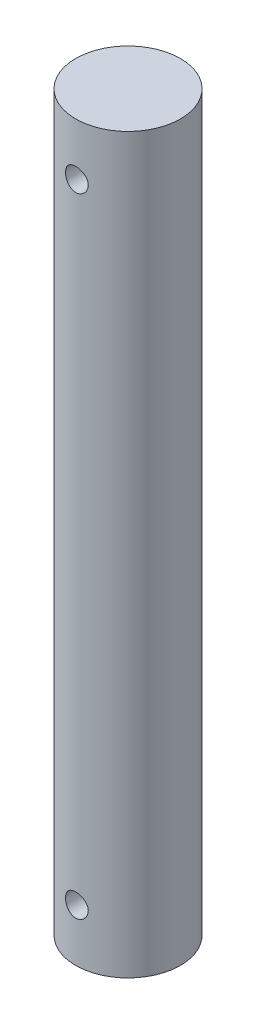
SolidWorks part; units mm, degrees
ref_plane "Front Plane" through (0, 0, 0) normal (0, 0, 1) x (1, 0, 0)
ref_plane "Top Plane" through (0, 0, 0) normal (0, 1, 0) x (1, 0, 0)
ref_plane "Right Plane" through (0, 0, 0) normal (1, 0, 0) x (0, 0, -1)
sketch "Sketch1" plane through (0, 0, 0) normal (0, 0, 1) x (1, 0, 0)
  line L1 (0, 0) -> (-15, 0)
  line L2 (0, 0) -> (0, 210)
  line L3 (0, 210) -> (-15, 210)
  line L4 (-15, 0) -> (-15, 210)
  dimension "D1" = 15
  dimension "D2" = 210
revolve "Revolve1" add sketch "Sketch1" angle 360 about L2
sketch "Sketch3" plane through (0, 0, 0) normal (0, 0, 1) x (1, 0, 0)
  line L0 (15, 0) -> (15, 210) construction
  line L1 (-15, 210) -> (15, 210) construction
  line L2 (-15, 210) -> (-15, 180) construction
  line L3 (-15, 180) -> (15, 180) construction
  line L4 (15, 210) -> (15, 180) construction
  line L5 (0, 210) -> (0, 180) construction
  circle A0 centre (0, 195) radius 3.25
  point P9 (0, 195)
  dimension "D2" = 6.5
  dimension "D1" = 30
extrude "Cut-Extrude1" cut sketch "Sketch3" against normal through all both and the other way through all
ref_plane "Plane1" through (0, 105, 0) normal (0, 1, 0) x (1, 0, 0)
mirror "Mirror1" about plane through (0, 105, 0) normal (0, 1, 0) of "Cut-Extrude1"
